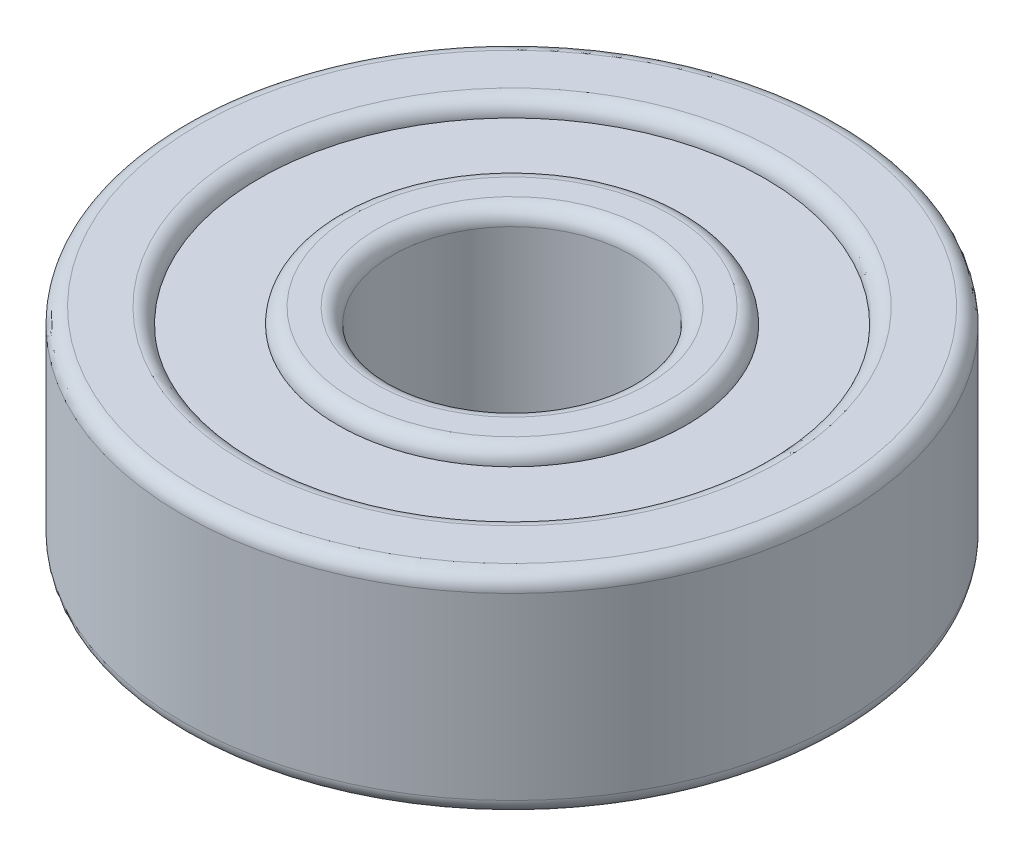
SolidWorks part; units mm, degrees
material "Alloy Steel"
ref_plane "Front" through (0, 0, 0) normal (0, 0, 1) x (1, 0, 0)
ref_plane "Top" through (0, 0, 0) normal (0, 1, 0) x (1, 0, 0)
ref_plane "Right" through (0, 0, 0) normal (1, 0, 0) x (0, 0, -1)
sketch "Sketch1" plane through (0, 0, 0) normal (0, 1, 0) x (1, 0, 0)
  circle A0 centre (0, 0) radius 11
  circle A1 centre (0, 0) radius 4
  dimension "D1" = 22
  dimension "D2" = 8
extrude "Boss-Extrude1" add sketch "Sketch1" along normal mid plane 7
sketch "Sketch2" plane through (0, 3.5, 0) normal (0, 1, 0) x (1, 0, 0)
  circle A0 centre (0, 0) radius 8.44
  circle A1 centre (0, 0) radius 5.82
  dimension "D1" = 11.64
  dimension "D2" = 16.88
extrude "Cut-Extrude1" cut sketch "Sketch2" against normal through all
sketch "Sketch3" plane through (0, 0, 0) normal (1, 0, 0) x (0, 0, -1)
  line L0 (-11, 0) -> (11, 0) construction
  line L1 (-11, 3.5) -> (-11, -3.5) construction
  line L2 (11, -3.5) -> (11, 3.5) construction
  line L3 (4, 8.4686) -> (4, -1.7841) construction
  line L4 (11, 8.4686) -> (11, -1.7841) construction
  line L5 (11, -3.5) -> (11, 3.5) construction
  line L7 (0, 8.4686) -> (0, -1.7841) construction
  circle A0 centre (7.27, 0) radius 2.33
  dimension "D2" = 4.66
  dimension "D1" = 3.27
revolve "Cut-Revolve1" cut sketch "Sketch3" angle 360 about L7
fillet "Fillet1" radius 0.508 4 edges at (0, -3.5, 8.44) (0, 3.5, 8.44) (0, -3.5, 11) (0, 3.5, 11)
fillet "Fillet2" radius 0.508 4 edges at (0, -3.5, 4) (0, -3.5, 5.82) (0, 3.5, 4) (0, 3.5, 5.82)
sketch "Sketch4" plane through (0, 0, 0) normal (1, 0, 0) x (0, 0, -1)
  line L0 (7.27, 2.33) -> (7.27, -2.33)
  line L1 (7.27, 8.5081) -> (7.27, -1.5343) construction
  arc A0 (5.82, 1.8239) -> (5.82, -1.8239) centre (7.27, 0) ccw construction
  arc A1 (7.27, 2.33) -> (7.27, -2.33) centre (7.27, 0) cw
  arc A3 (5.82, 1.8239) -> (5.82, -1.8239) centre (7.27, 0) ccw construction
revolve "Revolve1" add sketch "Sketch4" angle 360 about L1
pattern_circular "CirPattern2" count 7 over 360 about axis through (0, 0, 0) along (0, 1, 0) of bodies 106
ref_plane "Plane1" through (0, 2.015, 0) normal (0, -1, 0) x (1, 0, 0)
ref_plane "Plane2"
sketch "Sketch5" plane through (0, 0, 0) normal (0, 1, 0) x (1, 0, 0)
  circle A0 centre (0, 0) radius 5.82 construction
  circle A1 centre (0, 0) radius 8.44 construction
  circle A2 centre (0, 0) radius 5.82
  circle A3 centre (0, 0) radius 8.44
extrude "Boss-Extrude4" add sketch "Sketch5" along normal up to surface (0.9771 mm away) from surface at 2.0149 separate body starting at plane "Plane1"
mirror "Mirror1" about plane through (0, 0, 0) normal (0, 1, 0) of bodies 113
